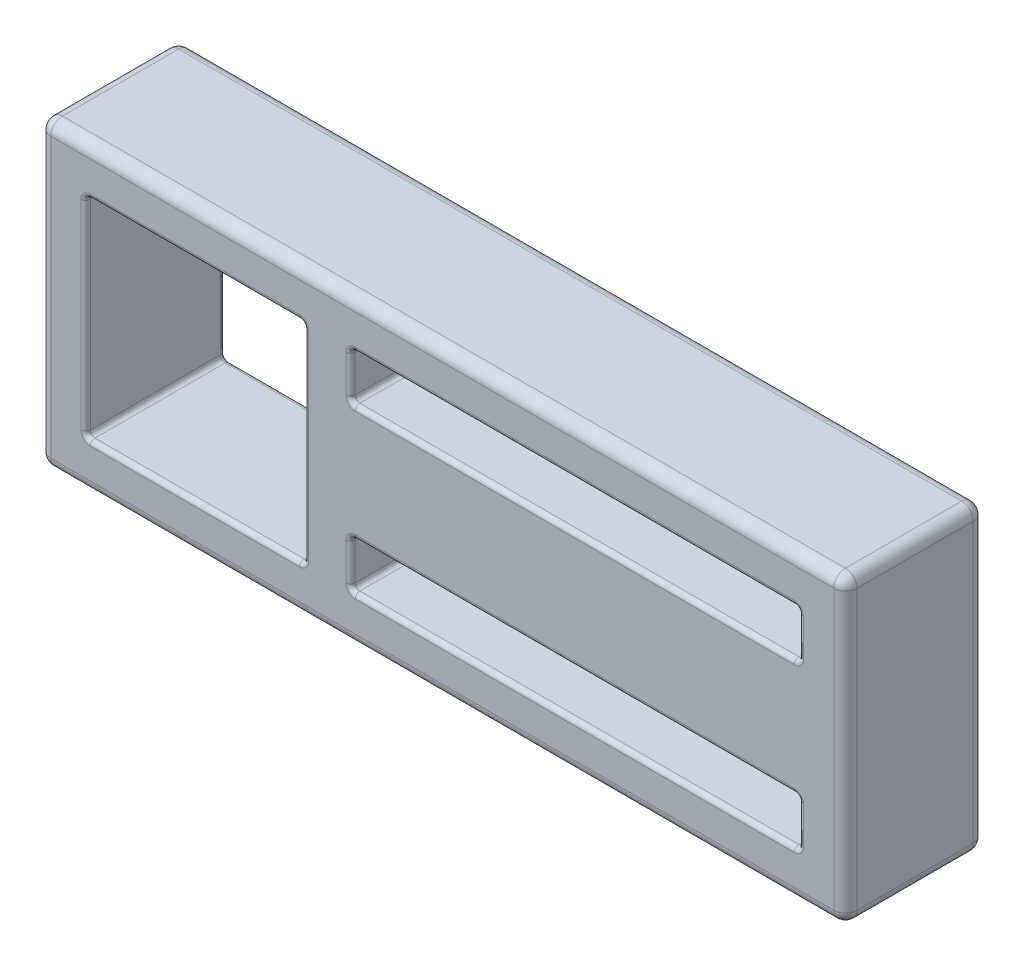
SolidWorks part; units mm, degrees
ref_plane "Front Plane" through (0, 0, 0) normal (0, 0, 1) x (1, 0, 0)
ref_plane "Top Plane" through (0, 0, 0) normal (0, 1, 0) x (1, 0, 0)
ref_plane "Right Plane" through (0, 0, 0) normal (1, 0, 0) x (0, 0, -1)
sketch "Sketch1" plane through (0, 0, 0) normal (0, 0, 1) x (1, 0, 0)
  line L0 (17.018, 13.97) -> (41.529, 13.97)
  line L1 (0, 0) -> (44.069, 0)
  line L2 (0, 0) -> (0, 16.51)
  line L3 (0, 16.51) -> (44.069, 16.51)
  line L4 (44.069, 0) -> (44.069, 16.51)
  line L5 (2.54, 13.97) -> (14.478, 13.97)
  line L6 (2.54, 13.97) -> (2.54, 2.54)
  line L7 (2.54, 2.54) -> (14.478, 2.54)
  line L8 (14.478, 13.97) -> (14.478, 2.54)
  line L9 (17.018, 5.08) -> (41.529, 5.08)
  line L10 (17.018, 5.08) -> (17.018, 2.54)
  line L11 (17.018, 2.54) -> (41.529, 2.54)
  line L12 (41.529, 5.08) -> (41.529, 2.54)
  line L13 (17.018, 13.97) -> (17.018, 11.43)
  line L14 (17.018, 11.43) -> (41.529, 11.43)
  line L15 (41.529, 13.97) -> (41.529, 11.43)
  point P9 (8.509, 2.54)
  dimension "D1" = 11.938
  dimension "D2" = 11.43
  dimension "D3" = 2.54
  dimension "D4" = 2.54
  dimension "D5" = 2.54
  dimension "D6" = 35.56
  dimension "D7" = 2.54
  dimension "D8" = 2.54
  dimension "D9" = 2.54
  dimension "D10" = 2.54
  dimension "D11" = 2.54
extrude "Boss-Extrude1" add sketch "Sketch1" along normal blind 7.62
fillet "Fillet1" radius 0.635 12 edges at (44.069, 8.255, 0) (44.069, 8.255, 7.62) (44.069, 0, 3.81) (22.0345, 16.51, 0) (22.0345, 0, 7.62) (22.0345, 0, 0) (0, 8.255, 0) (0, 8.255, 7.62) (22.0345, 16.51, 7.62) (0, 0, 3.81) (0, 16.51, 3.81) (44.069, 16.51, 3.81)
fillet "Fillet2" radius 0.254 36 edges at (29.2735, 2.54, 7.62) (29.2735, 2.54, 0) (29.2735, 5.08, 7.62) (29.2735, 5.08, 0) (41.529, 5.08, 3.81) (41.529, 3.81, 7.62) (41.529, 2.54, 3.81) (41.529, 3.81, 0) (17.018, 2.54, 3.81) (17.018, 3.81, 7.62) (17.018, 5.08, 3.81) (17.018, 3.81, 0) (41.529, 12.7, 7.62) (41.529, 12.7, 0) (29.2735, 13.97, 7.62) (41.529, 13.97, 3.81) (29.2735, 13.97, 0) (41.529, 11.43, 3.81) (29.2735, 11.43, 7.62) (29.2735, 11.43, 0) (17.018, 11.43, 3.81) (17.018, 12.7, 7.62) (17.018, 13.97, 3.81) (17.018, 12.7, 0) (8.509, 2.54, 7.62) (8.509, 2.54, 0) (8.509, 13.97, 7.62) (8.509, 13.97, 0) (14.478, 13.97, 3.81) (14.478, 8.255, 7.62) (14.478, 2.54, 3.81) (14.478, 8.255, 0) (2.54, 2.54, 3.81) (2.54, 8.255, 7.62) (2.54, 13.97, 3.81) (2.54, 8.255, 0)
